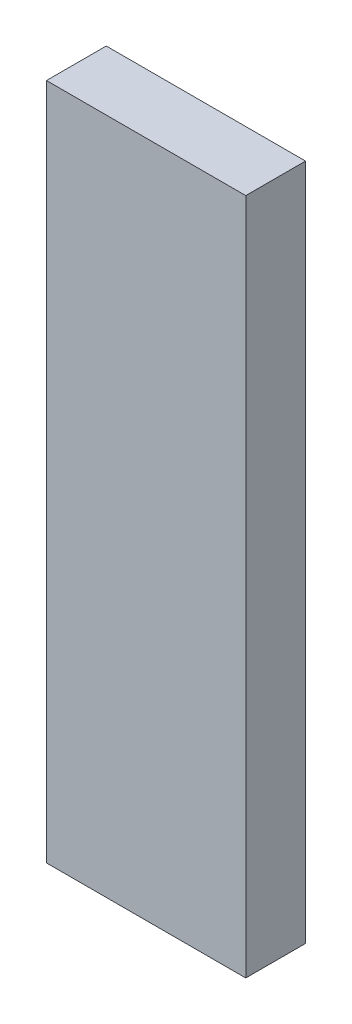
SolidWorks part; units mm, degrees
material "Klon"
ref_plane "Płaszczyzna przednia" through (0, 0, 0) normal (0, 0, 1) x (1, 0, 0)
ref_plane "Płaszczyzna górna" through (0, 0, 0) normal (0, 1, 0) x (1, 0, 0)
ref_plane "Płaszczyzna prawa" through (0, 0, 0) normal (1, 0, 0) x (0, 0, -1)
sketch "Szkic1" plane through (0, 0, 0) normal (0, 1, 0) x (1, 0, 0)
  line L1 (-25, -7.5) -> (25, -7.5)
  line L2 (-25, -7.5) -> (-25, 7.5)
  line L3 (-25, 7.5) -> (25, 7.5)
  line L4 (25, -7.5) -> (25, 7.5)
  line L5 (-25, -7.5) -> (25, 7.5) construction
  line L6 (-25, 7.5) -> (25, -7.5) construction
  point P0 (0, 0)
  dimension "D1" = 50
  dimension "D2" = 15
extrude "Dodanie-wyciągnięcie1" add sketch "Szkic1" along normal blind 170
